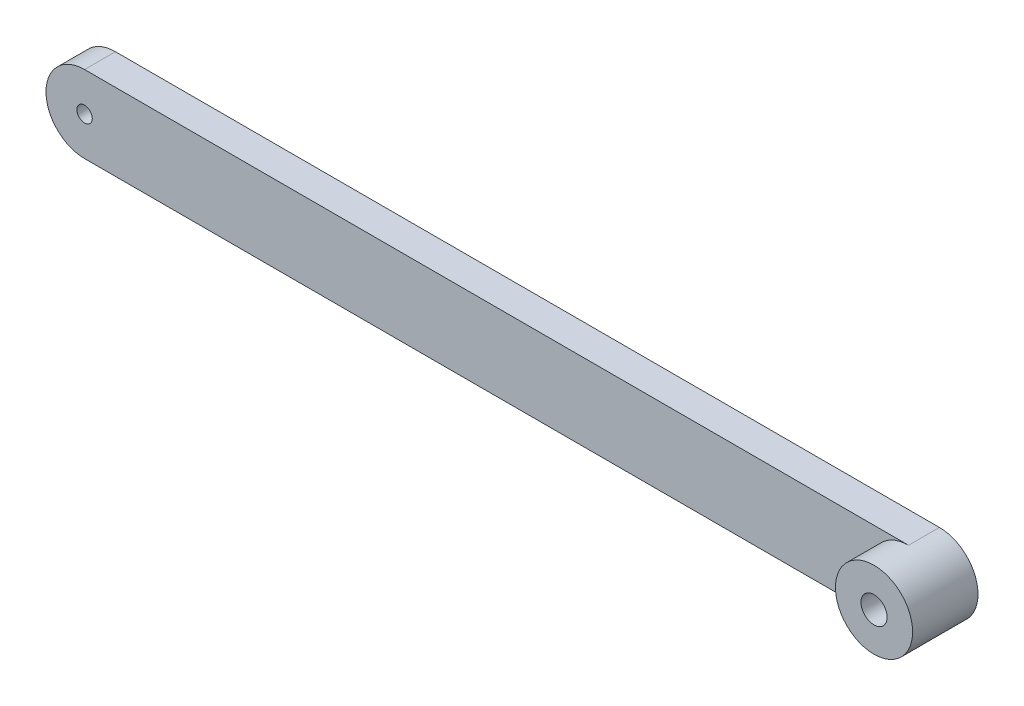
SolidWorks part; units mm, degrees
ref_plane "Plano frontal" through (0, 0, 0) normal (0, 0, 1) x (1, 0, 0)
ref_plane "Plano superior" through (0, 0, 0) normal (0, 1, 0) x (1, 0, 0)
ref_plane "Plano direito" through (0, 0, 0) normal (1, 0, 0) x (0, 0, -1)
sketch "Esboço1" plane through (0, 0, 0) normal (0, 0, 1) x (1, 0, 0)
  line L0 (-26.705, 0) -> (26.705, 0) construction
  line L1 (-26.705, 2.5) -> (26.705, 2.5)
  line L2 (-26.705, -2.5) -> (26.705, -2.5)
  arc A0 (-26.705, 2.5) -> (-26.705, -2.5) centre (-26.705, 0) ccw
  arc A1 (26.705, -2.5) -> (26.705, 2.5) centre (26.705, 0) ccw
  point P2 (0, 0)
  dimension "D2" = 5
  dimension "D1" = 53.41
extrude "Ressalto-extrusão1" add sketch "Esboço1" along normal blind 2
sketch "Esboço3" plane through (0, 0, 2) normal (0, 0, 1) x (1, 0, 0)
  circle A0 centre (26.705, 0) radius 2.5
  arc A2 (26.705, -2.5) -> (26.705, 2.5) centre (26.705, 0) ccw construction
extrude "Ressalto-extrusão2" add sketch "Esboço3" along normal blind 2.24
sketch "Esboço2" plane through (0, 0, 0) normal (0, 0, -1) x (-1, 0, 0)
  circle A0 centre (26.705, 0) radius 0.5
  arc A1 (26.705, -2.5) -> (26.705, 2.5) centre (26.705, 0) ccw construction
  dimension "D1" = 1
extrude "Corte-extrusão1" cut sketch "Esboço2" against normal through all
sketch "Esboço4" plane through (0, 0, 4.24) normal (0, 0, 1) x (1, 0, 0)
  circle A0 centre (26.705, 0) radius 0.85
  circle A1 centre (26.705, 0) radius 2.5 construction
  dimension "D1" = 1.7
extrude "Corte-extrusão2" cut sketch "Esboço4" against normal through all
